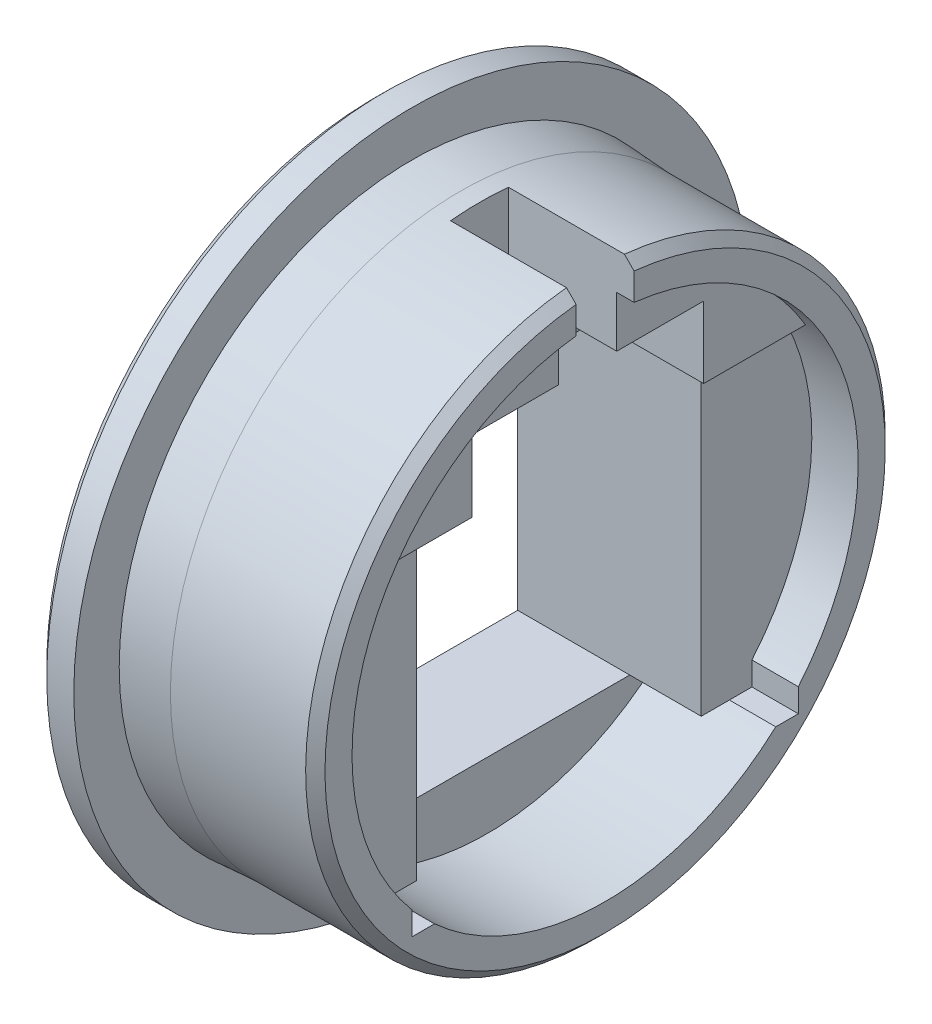
SolidWorks part; units mm, degrees
ref_plane "Ebene vorne" through (0, 0, 0) normal (0, 0, 1) x (1, 0, 0)
ref_plane "Ebene oben" through (0, 0, 0) normal (0, 1, 0) x (1, 0, 0)
ref_plane "Ebene rechts" through (0, 0, 0) normal (1, 0, 0) x (0, 0, -1)
sketch "Skizze1" plane through (0, 0, 0) normal (0, 1, 0) x (1, 0, 0)
  line L0 (-3.3698, 0) -> (19.5736, 0) construction
  line L1 (0, 0) -> (0, 17.5)
  line L2 (0, 17.5) -> (1.9, 17.5)
  line L3 (1.9, 17.5) -> (1.9, 15)
  line L4 (1.9, 15) -> (11.9, 15)
  line L7 (11.9, 15) -> (11.9, 13.1)
  line L8 (11.9, 13.1) -> (1.9, 13.1)
  line L9 (1.9, 13.1) -> (1.9, 0)
  line L10 (1.9, 0) -> (0, 0)
  dimension "D1" = 1.9
  dimension "D2" = 35
  dimension "D3" = 30
  dimension "D4" = 1.9
  dimension "D5" = 10
revolve "Rotation1" add sketch "Skizze1" angle 360 about L0
sketch "Skizze2" plane through (0, 0, 0) normal (-1, 0, 0) x (0, 0, 1)
  line L0 (0, 0) -> (0, -1.5) construction
  line L1 (-7.375, -9.675) -> (7.375, -9.675)
  line L2 (-7.375, -9.675) -> (-7.375, 6.675)
  line L3 (-7.375, 6.675) -> (7.375, 6.675)
  line L4 (7.375, -9.675) -> (7.375, 6.675)
  line L5 (-7.375, -9.675) -> (7.375, 6.675) construction
  line L6 (-7.375, 6.675) -> (7.375, -9.675) construction
  point P0 (0, -1.5)
  dimension "D1" = 16.35
  dimension "D2" = 14.75
  dimension "D3" = 1.5
extrude "Schnitt-Linear austragen1" cut sketch "Skizze2" against normal through all
sketch "Skizze3" plane through (1.9, 0, 0) normal (1, 0, 0) x (0, 0, -1)
  line L0 (-8.832, -9.675) -> (8.832, -9.675)
  circle A0 centre (0, 0) radius 13.1 construction
  circle A1 centre (0, 0) radius 13.1 construction
  arc A2 (-8.832, -9.675) -> (8.832, -9.675) centre (0, 0) ccw
extrude "Aufsatz-Linear austragen1" add sketch "Skizze3" along normal blind 3.9
sketch "Skizze4" plane through (1.9, 0, 0) normal (1, 0, 0) x (0, 0, -1)
  line L0 (-11.2718, 6.675) -> (11.2718, 6.675)
  arc A0 (8.832, -9.675) -> (-8.832, -9.675) centre (0, 0) ccw construction
  arc A1 (11.2718, 6.675) -> (-11.2718, 6.675) centre (0, 0) ccw
extrude "Aufsatz-Linear austragen2" add sketch "Skizze4" along normal blind 9.1
sketch "Skizze6" plane through (0, 0, 0) normal (0, 0, 1) x (1, 0, 0)
  line L0 (5.4, 6.675) -> (5.4, 11.625)
  line L1 (11, 6.675) -> (1.9, 6.675) construction
  line L2 (5.4, 11.625) -> (8.5, 11.625)
  line L3 (8.5, 11.625) -> (8.5, 10.375)
  line L4 (8.5, 10.375) -> (11, 10.375)
  line L6 (11, 10.375) -> (11, 6.675)
  line L7 (11, 6.675) -> (5.4, 6.675)
  line L8 (0, 17.5) -> (0, -17.5) construction
  dimension "D1" = 5.4
  dimension "D2" = 3.1
  dimension "D3" = 4.95
  dimension "D4" = 3.7
extrude "Schnitt-Linear austragen2" cut sketch "Skizze6" against normal mid plane 12
sketch "Skizze7" plane through (1.9, 0, 0) normal (1, 0, 0) x (0, 0, -1)
  line L2 (-11.2718, 6.675) -> (-7.375, 6.675) construction
  line L3 (-7.375, -9.675) -> (-7.375, 6.675) construction
  line L5 (7.375, 6.675) -> (11.2718, 6.675) construction
  line L6 (-11.2718, 6.675) -> (-7.375, 6.675)
  line L7 (-7.375, -9.675) -> (-7.375, 6.675)
  line L8 (-7.375, -9.675) -> (-8.832, -9.675) construction
  line L9 (8.832, -9.675) -> (7.375, -9.675) construction
  line L10 (7.375, 6.675) -> (7.375, -9.675) construction
  line L11 (7.375, 6.675) -> (7.375, -9.675)
  line L12 (8.832, -9.675) -> (7.375, -9.675)
  line L13 (-7.375, -9.675) -> (-8.832, -9.675)
  line L14 (7.375, 6.675) -> (11.2718, 6.675)
  arc A1 (-11.2718, 6.675) -> (-8.832, -9.675) centre (0, 0) ccw construction
  arc A3 (-11.2718, 6.675) -> (-8.832, -9.675) centre (0, 0) ccw
  arc A4 (8.832, -9.675) -> (11.2718, 6.675) centre (0, 0) ccw construction
  arc A5 (8.832, -9.675) -> (11.2718, 6.675) centre (0, 0) ccw
extrude "Aufsatz-Linear austragen3" add sketch "Skizze7" along normal blind 7.6
chamfer "Fase1" distance 0.5 angle 45 2 edges at (0, 0, 17.5) (11.9, 0, 15)
sketch "Skizze8" plane through (0, 0, 0) normal (-1, 0, 0) x (0, 0, 1)
  line L0 (-7.375, 6.675) -> (-7.375, -9.675) construction
  line L1 (7.375, 6.675) -> (-7.375, 6.675) construction
  line L2 (-6.875, 8.175) -> (-6.875, 9.175) construction
  text T0 "LAN" font "Century Gothic" height 5
  dimension "D1" = 0.5
  dimension "D2" = 2.5
  dimension "D3" = 1.5
extrude "Schnitt-Linear austragen3" cut sketch "Skizze8" against normal blind 0.4
sketch "Skizze10" plane through (11.9, 0, 0) normal (1, 0, 0) x (0, 0, -1)
  line L0 (-1.5, 10.375) -> (-1.5, 14.9248)
  line L1 (6, 10.375) -> (-6, 10.375) construction
  line L2 (-1.5, 10.375) -> (1.5, 10.375)
  line L3 (1.5, 10.375) -> (1.5, 14.9248)
  circle A0 centre (0, 0) radius 15 construction
  arc A1 (1.5, 14.9248) -> (-1.5, 14.9248) centre (0, 0) ccw
  point P6 (0, 10.375)
  dimension "D1" = 3
extrude "Schnitt-Linear austragen4" cut sketch "Skizze10" against normal up to surface (6.5 mm away) up to face at (5.4, 9.15, 0)
sketch "Skizze12" plane through (1.9, 0, 0) normal (1, 0, 0) x (0, 0, -1)
  line L0 (0, 0) -> (-11.6439, -9.7704) construction
  line L1 (0, 0) -> (11.6439, -9.7704) construction
  line L2 (0, 0) -> (0, 15.2) construction
  arc A0 (-11.6439, -9.7704) -> (11.6439, -9.7704) centre (0, 0) cw
  dimension "D1" = 15.2
  dimension "D2" = 260
sketch "Skizze11" plane through (1.9, 0, 0) normal (1, 0, 0) x (0, 0, -1)
  text T0 "VEB WGW SCHWARZENBERG IM KOMBINAT VEB MONSATOR " font "Century Gothic" height 1.5
extrude "Schnitt-Linear austragen5" [suppressed] cut sketch "Skizze11" against normal blind 0.2
sketch "Skizze13" plane through (11.9, 0, 0) normal (1, 0, 0) x (0, 0, -1)
  line L0 (10, -9.675) -> (-10, -9.675)
  line L1 (7.375, -9.675) -> (-7.375, -9.675) construction
  line L2 (0, 0) -> (0, -9.675) construction
  line L3 (-10, -9.675) -> (-10, -8.4623)
  line L4 (-10, -8.4623) -> (10, -8.4623)
  line L5 (10, -8.4623) -> (10, -9.675)
  arc A0 (-11.2718, 6.675) -> (-8.832, -9.675) centre (0, 0) ccw construction
  arc A1 (8.832, -9.675) -> (11.2718, 6.675) centre (0, 0) ccw construction
  dimension "D1" = 20
extrude "Schnitt-Linear austragen6" cut sketch "Skizze13" against normal up to surface (2.4 mm away) up to face at (9.5, -1.6084, -9.4396)
sketch "Skizze14" plane through (0, 0, 0) normal (0, 0, 1) x (1, 0, 0)
  line L0 (4.4, 15) -> (1.9, 15.15)
  line L1 (5.4, 15) -> (1.9, 15) construction
  line L2 (1.9, -17.5) -> (1.9, 17.5) construction
  line L3 (1.9, 15.15) -> (1.9, 15)
  line L4 (1.9, 15) -> (4.4, 15)
  point P6 (1.9, 15.075)
  point P8 (0, 0)
  dimension "D1" = 0.15
  dimension "D2" = 2.5
revolve "Rotation2" add sketch "Skizze14" angle 360 about axis through (-3.3698, 0, 0) along (-1, 0, 0)
